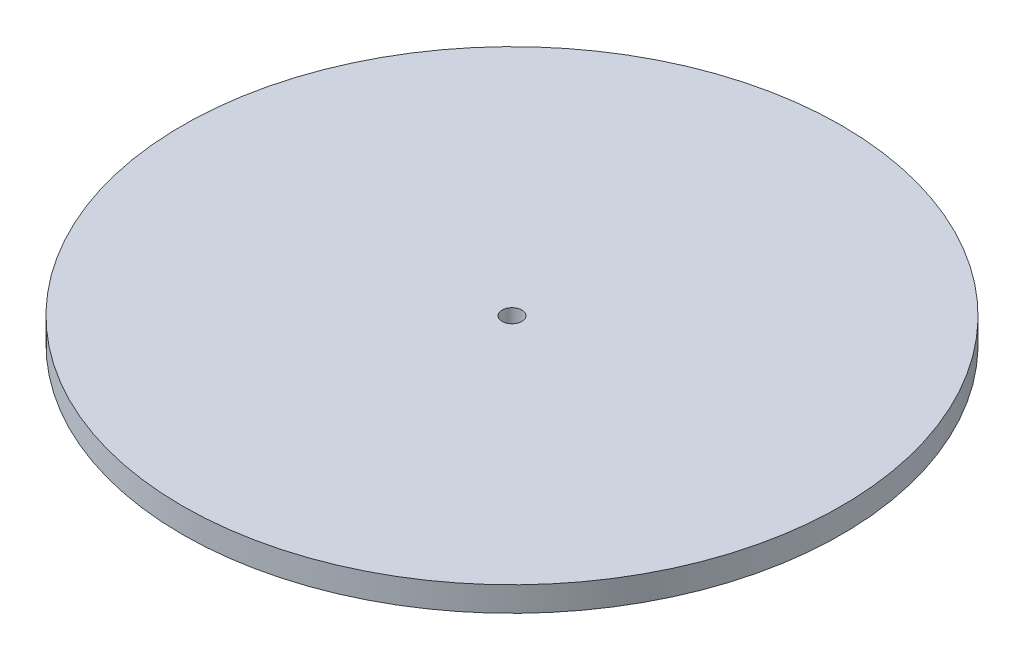
SolidWorks part; units mm, degrees
ref_plane "Front Plane" through (0, 0, 0) normal (0, 0, 1) x (1, 0, 0)
ref_plane "Top Plane" through (0, 0, 0) normal (0, 1, 0) x (1, 0, 0)
ref_plane "Right Plane" through (0, 0, 0) normal (1, 0, 0) x (0, 0, -1)
sketch "Sketch3" plane through (0, 0, 0) normal (0, 0, 1) x (1, 0, 0)
  line L0 (37, 9.4028) -> (37, 13.4028) construction
  line L1 (37, 13.4028) -> (0, 13.4028) construction
  line L2 (0, 13.4028) -> (0, 0) construction
  line L4 (1.2, 13.4028) -> (1.2, 8.4028)
  line L5 (1.2, 8.4028) -> (0, 8.4028)
  line L6 (0, 8.4028) -> (0, 0)
  line L7 (37, 9.4028) -> (40, 9.4028) construction
  line L8 (40, 9.4028) -> (40, 13.4028) construction
  line L9 (40, 13.4028) -> (1.2, 13.4028)
  line L10 (37, 9.4028) -> (37, 10.4028)
  line L11 (37, 10.4028) -> (40, 10.4028)
  line L12 (40, 10.4028) -> (40, 13.4028)
  spline S0 degree 8 poles (-3.7, 0.146) (1.8386, -0.2792) (7.3772, -0.0629) (12.9159, 1.3221) (18.4545, 2.9707) (23.9931, 4.8069) (29.5317, 6.7551) (35.0704, 8.7117) (40.609, 10.6859) knots 0 0 0 0 0 0 0 0 0 1 1 1 1 1 1 1 1 1 construction
  spline S1 degree 8 poles (0, 0) (4.625, 0.0011) (9.25, 0.5462) (13.875, 1.6758) (18.5, 3.0429) (23.125, 4.5485) (27.75, 6.1395) (32.375, 7.7632) (37, 9.4028) knots 0.083505 0.083505 0.083505 0.083505 0.083505 0.083505 0.083505 0.083505 0.083505 0.91855 0.91855 0.91855 0.91855 0.91855 0.91855 0.91855 0.91855 0.91855
  dimension "D1" = 3
  dimension "D2" = 1.2
  dimension "D3" = 5
  dimension "D4" = 3
  dimension "D5" = 40
  dimension "D6" = 9.4028
  dimension "D7" = 37
  dimension "D8" = 4
revolve "Revolve4" add sketch "Sketch3" angle 360 about L2
sketch "Sketch5" plane through (0, 13.4028, 0) normal (0, 1, 0) x (1, 0, 0)
  circle A0 centre (0, 0) radius 1.2
  circle A2 centre (0, 0) radius 1.2 construction
extrude "Cut-Extrude1" cut sketch "Sketch5" against normal through all
